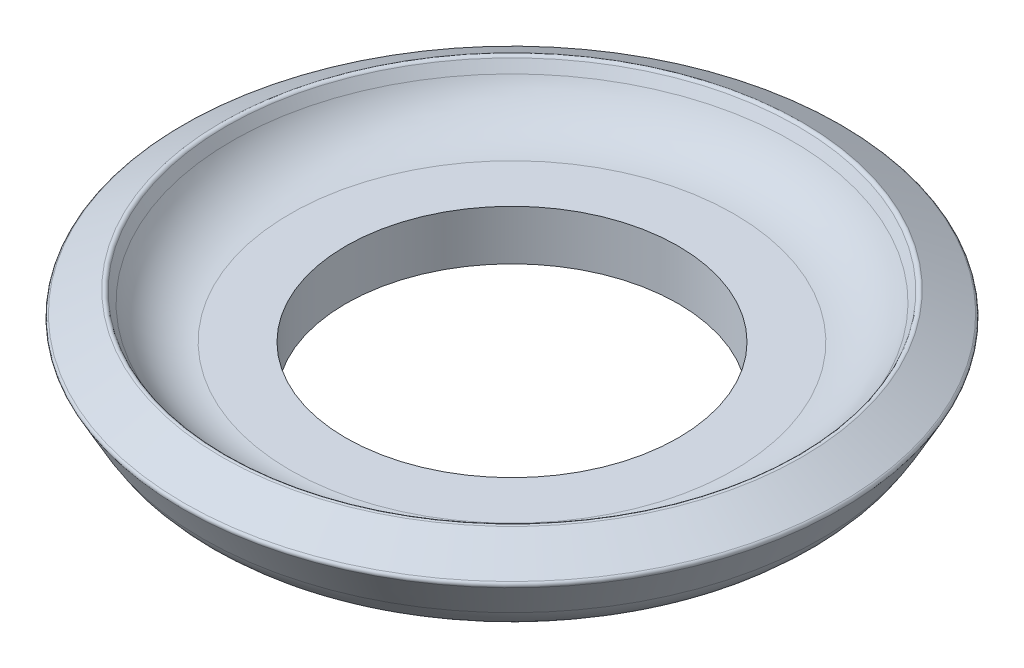
SolidWorks part; units mm, degrees
material "S235JR"
ref_plane "Front Plane" through (0, 0, 0) normal (0, 0, 1) x (1, 0, 0)
ref_plane "Top Plane" through (0, 0, 0) normal (0, 1, 0) x (1, 0, 0)
ref_plane "Right Plane" through (0, 0, 0) normal (1, 0, 0) x (0, 0, -1)
sketch "Sketch1" plane through (0, 0, 0) normal (0, 0, 1) x (1, 0, 0)
  line L0 (5, 1.1764) -> (7.5581, 1.1764)
  line L1 (9.3053, 2.2032) -> (9.9013, 3.2731)
  line L2 (9.8626, 3.4091) -> (8.7269, 4.0417)
  line L3 (8.5908, 4.003) -> (8.4238, 3.7032)
  line L4 (6.6766, 2.6764) -> (5, 2.6764)
  line L5 (0, 4.3712) -> (0, -2.8142) construction
  line L6 (5, 2.6764) -> (5, 1.1764)
  arc A0 (7.5581, 1.1764) -> (9.3053, 2.2032) centre (7.5581, 3.1764) ccw
  arc A1 (8.4238, 3.7032) -> (6.6766, 2.6764) centre (6.6766, 4.6764) cw
  arc A2 (9.8626, 3.4091) -> (9.9013, 3.2731) centre (9.8139, 3.3218) cw
  arc A3 (8.7269, 4.0417) -> (8.5908, 4.003) centre (8.6782, 3.9543) ccw
  point P11 (8.7334, 1.1764)
  point P14 (7.8519, 2.6764)
  point P17 (9.9499, 3.3605)
  point P20 (8.6395, 4.0904)
  dimension "D7" = 2
  dimension "D8" = 0.1
  dimension "D4" = 1.5
  dimension "D5" = 2.5
  dimension "D6" = 1.5
revolve "Revolve1" add sketch "Sketch1" angle 360 about L5
